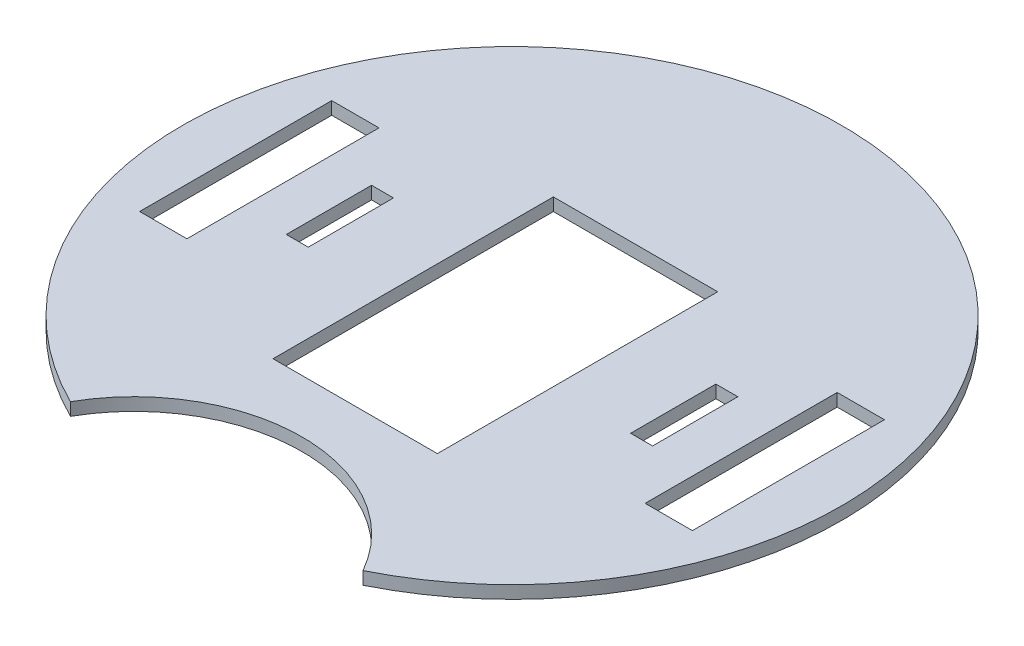
SolidWorks part; units mm, degrees
ref_plane "Front Plane" through (0, 0, 0) normal (0, 0, 1) x (1, 0, 0)
ref_plane "Top Plane" through (0, 0, 0) normal (0, 1, 0) x (1, 0, 0)
ref_plane "Right Plane" through (0, 0, 0) normal (1, 0, 0) x (0, 0, -1)
sketch "Sketch1" plane through (0, 0, 0) normal (0, 1, 0) x (1, 0, 0)
  line L0 (0, -86.0416) -> (-33.2911, -67.2064) construction
  line L1 (0, -86.0416) -> (0, 0) construction
  arc A0 (33.2911, -67.2064) -> (-33.2911, -67.2064) centre (0, 0) ccw
  arc A1 (33.2911, -67.2064) -> (-33.2911, -67.2064) centre (0, -86.0416) ccw
  dimension "D1" = 150
  dimension "D2" = 76.5
  dimension "D3" = 60.5
extrude "Boss-Extrude1" add sketch "Sketch1" along normal blind 2.9
sketch "solenoid placement" plane through (0, 2.9, 0) normal (0, 1, 0) x (1, 0, 0)
  line L0 (0, 0) -> (0, -36) construction
  line L1 (0, -36) -> (0, -47.7916) construction
  line L2 (-19, -36) -> (19, -36) construction
  line L3 (-19, -36) -> (-19, 28.4) construction
  line L4 (-19, 28.4) -> (19, 28.4) construction
  line L5 (19, -36) -> (19, 28.4) construction
  line L6 (-18.7, 28.1) -> (18.7, 28.1)
  line L7 (18.7, -35.7) -> (18.7, 28.1)
  line L8 (-18.7, -35.7) -> (18.7, -35.7)
  line L9 (-18.7, -35.7) -> (-18.7, 28.1)
  circle A1 centre (0, 0) radius 75 construction
  arc A2 (33.2911, -67.2064) -> (-33.2911, -67.2064) centre (0, 0) ccw construction
  arc A3 (33.2911, -67.2064) -> (-33.2911, -67.2064) centre (0, -86.0416) ccw construction
  dimension "D1" = 64.4
  dimension "D2" = 36
  dimension "D3" = 0.3
  dimension "D4" = 38
extrude "Cut-Extrude1" cut sketch "solenoid placement" against normal through all
sketch "Sketch2" plane through (0, 2.9, 0) normal (0, 1, 0) x (1, 0, 0)
  line L0 (52.4375, -21.5538) -> (52.4375, 21.5538) construction
  line L1 (-62.5975, -21.5538) -> (-52.4375, -21.5538) construction
  line L2 (-62.5975, -21.5538) -> (-62.5975, 21.5538) construction
  line L3 (-62.5975, 21.5538) -> (-52.4375, 21.5538) construction
  line L4 (-52.4375, -21.5538) -> (-52.4375, 21.5538) construction
  line L5 (62.5975, 21.5538) -> (52.4375, 21.5538) construction
  line L6 (62.5975, -21.5538) -> (62.5975, 21.5538) construction
  line L7 (62.5975, -21.5538) -> (52.4375, -21.5538) construction
  line L8 (62.8975, -21.8538) -> (62.8975, 21.8538)
  line L9 (62.8975, -21.8538) -> (52.1375, -21.8538)
  line L10 (52.1375, -21.8538) -> (52.1375, 21.8538)
  line L11 (62.8975, 21.8538) -> (52.1375, 21.8538)
  line L12 (0, 0) -> (0, 75) construction
  line L13 (-62.8975, 21.8538) -> (-52.1375, 21.8538)
  line L14 (-52.1375, -21.8538) -> (-52.1375, 21.8538)
  line L15 (-62.8975, -21.8538) -> (-52.1375, -21.8538)
  line L16 (-62.8975, -21.8538) -> (-62.8975, 21.8538)
  arc A0 (33.2911, -67.2064) -> (-33.2911, -67.2064) centre (0, 0) ccw construction
  dimension "D1" = 0.3
extrude "Cut-Extrude2" cut sketch "Sketch2" against normal through all
sketch "Sketch3" plane through (0, 2.9, 0) normal (0, 1, 0) x (1, 0, 0)
  line L0 (-41.6799, -9.7) -> (-36.6799, -9.7)
  line L1 (-41.9799, -10) -> (-36.3799, -10) construction
  line L2 (-41.9799, -10) -> (-41.9799, 10) construction
  line L3 (-41.9799, 10) -> (-36.3799, 10) construction
  line L4 (-36.3799, -10) -> (-36.3799, 10) construction
  line L5 (-36.6799, -9.7) -> (-36.6799, 9.7)
  line L6 (-41.6799, 9.7) -> (-36.6799, 9.7)
  line L7 (-41.6799, -9.7) -> (-41.6799, 9.7)
  line L8 (0, 0) -> (0, 75) construction
  line L9 (36.3799, -10) -> (36.3799, 10) construction
  line L10 (41.9799, 10) -> (36.3799, 10) construction
  line L11 (41.9799, -10) -> (41.9799, 10) construction
  line L12 (41.9799, -10) -> (36.3799, -10) construction
  line L13 (41.6799, -9.7) -> (41.6799, 9.7)
  line L14 (41.6799, 9.7) -> (36.6799, 9.7)
  line L15 (36.6799, -9.7) -> (36.6799, 9.7)
  line L16 (41.6799, -9.7) -> (36.6799, -9.7)
  arc A0 (33.2911, -67.2064) -> (-33.2911, -67.2064) centre (0, 0) ccw construction
  dimension "D1" = 0.3
extrude "Cut-Extrude3" cut sketch "Sketch3" against normal through all
equation "\"smallPulleyTeeth\"= 15"
equation "\"largePulleyTeeth\"= 30"
equation "\"eighthThick\"= 2.9mm"
equation "\"sixteenthThick\" = 1.7mm"
equation "\"wheelEighthThick\"=3.0mm"
equation "\"quarterThick\"=5.6mm"
equation "\"OD\" = 150mm"
equation "\"puckAngle\" = 60.5deg"
equation "\"D1@Sketch1\"=\"OD\""
equation "\"puckDiam\" = 76.5mm"
equation "\"D2@Sketch1\"=\"puckDiam\""
equation "\"D3@Sketch1\"=\"puckAngle\""
equation "\"D1@Boss-Extrude1\"=\"eighthThick\""
equation "\"axlePress\" = 5.8mm"
equation "\"press\" = 0.3mm"
equation "\"D1@Sketch3\"=\"press\""
equation "\"wheelClear\" = 0.3mm"
equation "\"D1@Sketch2\"=\"wheelClear\""
